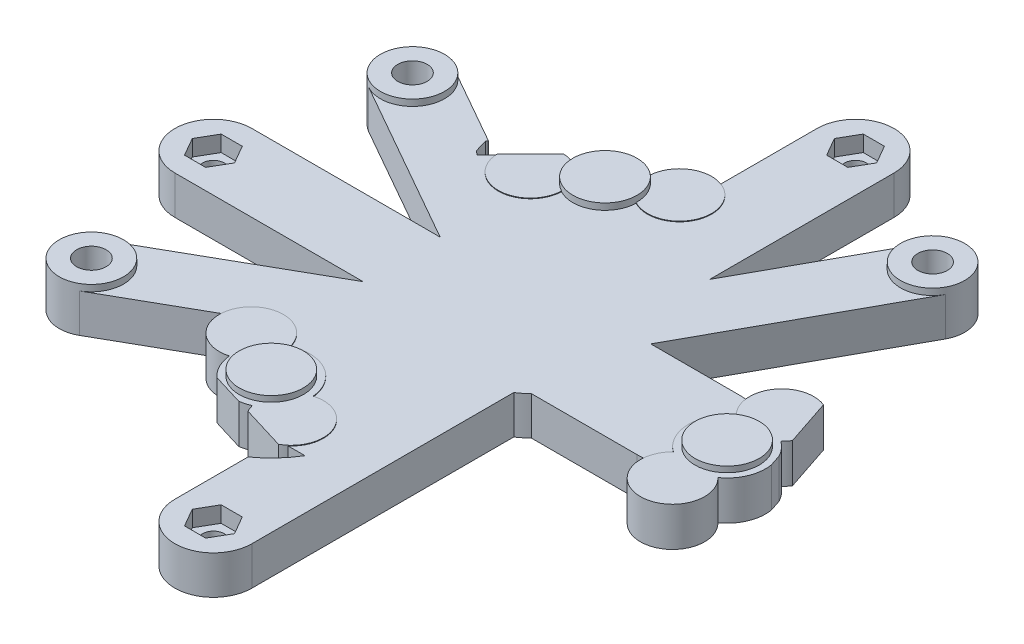
SolidWorks part; units mm, degrees
other "Fixed Star Plate Print Blank"
ref_plane "Front Plane" through (0, 0, 0) normal (0, 0, 1) x (1, 0, 0)
ref_plane "Top Plane" through (0, 0, 0) normal (0, 1, 0) x (1, 0, 0)
ref_plane "Right Plane" through (0, 0, 0) normal (1, 0, 0) x (0, 0, -1)
sketch3d "Base Outline Sketch datum points"
  point P0 (0, -71, 0)
  point P1 (10, -71, 0)
  point P2 (0, -71, -10)
ref_plane "Base Outline Sketch plane" through (0, -71, 0) normal (0, 1, 0) x (1, 0, 0)
sketch "Base Outline Sketch" plane through (0, -71, 0) normal (0, 1, 0) x (1, 0, 0)
  line L0 (-32.2917, 8) -> (-46.1853, 8)
  line L1 (-24.4227, 13.1376) -> (-22.0154, 5.909)
  line L2 (-20.9711, 2.7735) -> (-20.3706, 0.9703)
  line L3 (-48.7418, -8) -> (-32.2917, -8)
  line L4 (-50.2917, -50) -> (-50.2917, -9.2195)
  line L5 (-62.2917, -38.6002) -> (-62.2917, -50)
  line L6 (-58.0273, -34) -> (-60.6452, -34)
  line L7 (-61.5389, -34.6217) -> (-68.3642, -32.542)
  line L8 (-70.4166, -31.9166) -> (-75.3281, -30.42)
  line L9 (-97.8216, -29.3473) -> (-83.633, -21.2856)
  line L10 (-76.9729, -6) -> (-102.7617, -20.6527)
  line L11 (-106.2917, -6) -> (-76.9729, -6)
  line L12 (-76.9729, 6) -> (-106.2917, 6)
  line L13 (-102.7617, 20.6527) -> (-76.9729, 6)
  line L14 (-86.2562, 22.776) -> (-97.8216, 29.3473)
  line L15 (-86.2562, 22.776) -> (-86.3054, 22.6772)
  line L16 (-86.3054, 22.6772) -> (-86.3838, 22.4486)
  line L17 (-85.7572, 20.4132) -> (-85.2034, 19.9887)
  line L18 (-85.2034, 19.9887) -> (-83.8108, 21.3866)
  line L19 (-83.633, 21.2856) -> (-83.8108, 21.3866)
  line L20 (-83.6495, 21.5484) -> (-78.4893, 26.7281)
  line L21 (-62.2917, 50) -> (-62.2917, 34.9546)
  line L22 (-50.2917, 21.2843) -> (-50.2917, 50)
  line L23 (-38.6727, 42.4096) -> (-50.2917, 21.2843)
  line L24 (-46.1853, 8) -> (-29.9106, 37.5904)
  circle A0 centre (-71.2917, -25.9808) radius 3.95
  circle A1 centre (-63.9304, -30.2308) radius 1.6
  circle A2 centre (-26.2917, 0) radius 3.95
  circle A3 centre (-56.2917, -50) radius 3.1
  circle A4 centre (-26.2917, -8.5) radius 1.6
  circle A5 centre (-78.6529, -21.7308) radius 1.6
  circle A6 centre (-100.2917, -25) radius 2.3
  circle A7 centre (-71.2917, 25.9808) radius 3.95
  circle A8 centre (-34.2917, 40) radius 2.3
  circle A9 centre (-26.2917, 8.5) radius 1.6
  circle A10 centre (-63.9304, 30.2308) radius 1.6
  circle A11 centre (-56.2917, 50) radius 3.1
  circle A12 centre (-78.6529, 21.7308) radius 1.6
  circle A13 centre (-106.2917, 0) radius 3.1
  circle A14 centre (-100.2917, 25) radius 2.3
  arc A15 (-31.2594, 7.9331) -> (-32.2917, 8) centre (-32.2917, 0) ccw
  arc A16 (-24.4227, 13.1376) -> (-31.2594, 7.9331) centre (-26.2917, 8.5) ccw
  arc A17 (-22.8248, 4.8971) -> (-22.0154, 5.909) centre (-26.2917, 8.5) ccw
  arc A18 (-20.9711, 2.7735) -> (-22.8248, 4.8971) centre (-26.2917, 0) ccw
  arc A19 (-22.8248, -4.8971) -> (-20.3706, 0.9703) centre (-26.2917, 0) ccw
  arc A20 (-31.2594, -7.9331) -> (-22.8248, -4.8971) centre (-26.2917, -8.5) ccw
  arc A21 (-32.2917, -8) -> (-31.2594, -7.9331) centre (-32.2917, 0) ccw
  arc A22 (-50.2917, -9.2195) -> (-48.7418, -8) centre (-56.2917, 0) ccw
  arc A23 (-62.2917, -50) -> (-50.2917, -50) centre (-56.2917, -50) ccw
  arc A24 (-62.2917, -38.6002) -> (-58.0273, -34) centre (-71.2917, -25.9808) ccw
  arc A25 (-61.5389, -34.6217) -> (-60.6452, -34) centre (-63.9304, -30.2308) ccw
  arc A26 (-68.7841, -31.4316) -> (-68.3642, -32.542) centre (-63.9304, -30.2308) ccw
  arc A27 (-70.4166, -31.9166) -> (-68.7841, -31.4316) centre (-71.2917, -25.9808) ccw
  arc A28 (-77.266, -26.5346) -> (-75.3281, -30.42) centre (-71.2917, -25.9808) ccw
  arc A29 (-83.633, -21.2856) -> (-77.266, -26.5346) centre (-78.6529, -21.7308) ccw
  arc A30 (-100.2917, -30) -> (-97.8216, -29.3473) centre (-100.2917, -25) ccw
  arc A31 (-102.7617, -20.6527) -> (-100.2917, -30) centre (-100.2917, -25) ccw
  arc A32 (-106.2917, 6) -> (-106.2917, -6) centre (-106.2917, 0) ccw
  arc A33 (-97.8216, 29.3473) -> (-102.7617, 20.6527) centre (-100.2917, 25) ccw
  arc A34 (-86.3838, 22.4486) -> (-85.7572, 20.4132) centre (-71.2917, 25.9808) ccw
  arc A35 (-83.6495, 21.5484) -> (-83.633, 21.2856) centre (-78.6529, 21.7308) ccw
  arc A36 (-76.2892, 26.1368) -> (-78.4893, 26.7281) centre (-78.6529, 21.7308) ccw
  arc A37 (-68.928, 30.3868) -> (-76.2892, 26.1368) centre (-71.2917, 25.9808) ccw
  arc A38 (-68.7841, 31.4316) -> (-68.928, 30.3868) centre (-63.9304, 30.2308) ccw
  arc A39 (-62.2917, 34.9546) -> (-68.7841, 31.4316) centre (-63.9304, 30.2308) ccw
  arc A40 (-50.2917, 50) -> (-62.2917, 50) centre (-56.2917, 50) ccw
  arc A41 (-29.9106, 37.5904) -> (-38.6727, 42.4096) centre (-34.2917, 40) ccw
extrude "Base Outline" add sketch "Base Outline Sketch" along normal blind 1.4 separate body
sketch3d "Interface Profile 2 Sketch datum points"
  point P0 (0, -69.6, 0)
  point P1 (10, -69.6, 0)
  point P2 (0, -69.6, -10)
ref_plane "Interface Profile 2 Sketch plane" through (0, -69.6, 0) normal (0, 1, 0) x (1, 0, 0)
sketch "Interface Profile 2 Sketch" plane through (0, -69.6, 0) normal (0, 1, 0) x (1, 0, 0)
  line L0 (-32.2917, 8) -> (-46.1853, 8)
  line L1 (-24.4227, 13.1376) -> (-22.0154, 5.909)
  line L2 (-20.9711, 2.7735) -> (-20.3706, 0.9703)
  line L3 (-48.7418, -8) -> (-32.2917, -8)
  line L4 (-50.2917, -50) -> (-50.2917, -9.2195)
  line L5 (-62.2917, -38.6002) -> (-62.2917, -50)
  line L6 (-58.0273, -34) -> (-60.6452, -34)
  line L7 (-61.5389, -34.6217) -> (-68.3642, -32.542)
  line L8 (-70.4166, -31.9166) -> (-75.3281, -30.42)
  line L9 (-97.8216, -29.3473) -> (-83.633, -21.2856)
  line L10 (-76.9729, -6) -> (-102.7617, -20.6527)
  line L11 (-106.2917, -6) -> (-76.9729, -6)
  line L12 (-76.9729, 6) -> (-106.2917, 6)
  line L13 (-102.7617, 20.6527) -> (-76.9729, 6)
  line L14 (-86.2562, 22.776) -> (-97.8216, 29.3473)
  line L15 (-86.2562, 22.776) -> (-86.3054, 22.6772)
  line L16 (-86.3054, 22.6772) -> (-86.3838, 22.4486)
  line L17 (-85.7572, 20.4132) -> (-85.2034, 19.9887)
  line L18 (-85.2034, 19.9887) -> (-83.8108, 21.3866)
  line L19 (-83.633, 21.2856) -> (-83.8108, 21.3866)
  line L20 (-83.6495, 21.5484) -> (-78.4893, 26.7281)
  line L21 (-62.2917, 50) -> (-62.2917, 34.9546)
  line L22 (-50.2917, 21.2843) -> (-50.2917, 50)
  line L23 (-38.6727, 42.4096) -> (-50.2917, 21.2843)
  line L24 (-46.1853, 8) -> (-29.9106, 37.5904)
  circle A0 centre (-71.2917, -25.9808) radius 3.95
  circle A1 centre (-63.9304, -30.2308) radius 1.6
  circle A2 centre (-26.2917, 0) radius 3.95
  circle A3 centre (-56.2917, -50) radius 1.7
  circle A4 centre (-56.2917, 50) radius 1.7
  circle A5 centre (-106.2917, 0) radius 1.7
  circle A6 centre (-26.2917, -8.5) radius 1.6
  circle A7 centre (-78.6529, -21.7308) radius 1.6
  circle A8 centre (-100.2917, -25) radius 2.3
  circle A9 centre (-71.2917, 25.9808) radius 3.95
  circle A10 centre (-34.2917, 40) radius 2.3
  circle A11 centre (-26.2917, 8.5) radius 1.6
  circle A12 centre (-63.9304, 30.2308) radius 1.6
  circle A13 centre (-78.6529, 21.7308) radius 1.6
  circle A14 centre (-100.2917, 25) radius 2.3
  arc A15 (-31.2594, 7.9331) -> (-32.2917, 8) centre (-32.2917, 0) ccw
  arc A16 (-24.4227, 13.1376) -> (-31.2594, 7.9331) centre (-26.2917, 8.5) ccw
  arc A17 (-22.8248, 4.8971) -> (-22.0154, 5.909) centre (-26.2917, 8.5) ccw
  arc A18 (-20.9711, 2.7735) -> (-22.8248, 4.8971) centre (-26.2917, 0) ccw
  arc A19 (-22.8248, -4.8971) -> (-20.3706, 0.9703) centre (-26.2917, 0) ccw
  arc A20 (-31.2594, -7.9331) -> (-22.8248, -4.8971) centre (-26.2917, -8.5) ccw
  arc A21 (-32.2917, -8) -> (-31.2594, -7.9331) centre (-32.2917, 0) ccw
  arc A22 (-50.2917, -9.2195) -> (-48.7418, -8) centre (-56.2917, 0) ccw
  arc A23 (-62.2917, -50) -> (-50.2917, -50) centre (-56.2917, -50) ccw
  arc A24 (-62.2917, -38.6002) -> (-58.0273, -34) centre (-71.2917, -25.9808) ccw
  arc A25 (-61.5389, -34.6217) -> (-60.6452, -34) centre (-63.9304, -30.2308) ccw
  arc A26 (-68.7841, -31.4316) -> (-68.3642, -32.542) centre (-63.9304, -30.2308) ccw
  arc A27 (-70.4166, -31.9166) -> (-68.7841, -31.4316) centre (-71.2917, -25.9808) ccw
  arc A28 (-77.266, -26.5346) -> (-75.3281, -30.42) centre (-71.2917, -25.9808) ccw
  arc A29 (-83.633, -21.2856) -> (-77.266, -26.5346) centre (-78.6529, -21.7308) ccw
  arc A30 (-100.2917, -30) -> (-97.8216, -29.3473) centre (-100.2917, -25) ccw
  arc A31 (-102.7617, -20.6527) -> (-100.2917, -30) centre (-100.2917, -25) ccw
  arc A32 (-106.2917, 6) -> (-106.2917, -6) centre (-106.2917, 0) ccw
  arc A33 (-97.8216, 29.3473) -> (-102.7617, 20.6527) centre (-100.2917, 25) ccw
  arc A34 (-86.3838, 22.4486) -> (-85.7572, 20.4132) centre (-71.2917, 25.9808) ccw
  arc A35 (-83.6495, 21.5484) -> (-83.633, 21.2856) centre (-78.6529, 21.7308) ccw
  arc A36 (-76.2892, 26.1368) -> (-78.4893, 26.7281) centre (-78.6529, 21.7308) ccw
  arc A37 (-68.928, 30.3868) -> (-76.2892, 26.1368) centre (-71.2917, 25.9808) ccw
  arc A38 (-68.7841, 31.4316) -> (-68.928, 30.3868) centre (-63.9304, 30.2308) ccw
  arc A39 (-62.2917, 34.9546) -> (-68.7841, 31.4316) centre (-63.9304, 30.2308) ccw
  arc A40 (-50.2917, 50) -> (-62.2917, 50) centre (-56.2917, 50) ccw
  arc A41 (-29.9106, 37.5904) -> (-38.6727, 42.4096) centre (-34.2917, 40) ccw
extrude "Interface Profile 2" add sketch "Interface Profile 2 Sketch" along normal blind 0.1
sketch3d "Interface Profile 3 Sketch datum points"
  point P0 (0, -69.5, 0)
  point P1 (10, -69.5, 0)
  point P2 (0, -69.5, -10)
ref_plane "Interface Profile 3 Sketch plane" through (0, -69.5, 0) normal (0, 1, 0) x (1, 0, 0)
sketch "Interface Profile 3 Sketch" plane through (0, -69.5, 0) normal (0, 1, 0) x (1, 0, 0)
  line L0 (-70.8027, -29.9004) -> (-74.9306, -27.5171)
  line L1 (-23.1417, 2.3833) -> (-23.1417, -2.3833)
  line L2 (-74.9306, 27.5171) -> (-70.8027, 29.9004)
  line L3 (-32.2917, 8) -> (-46.1853, 8)
  line L4 (-24.4227, 13.1376) -> (-22.0154, 5.909)
  line L5 (-20.9711, 2.7735) -> (-20.3706, 0.9703)
  line L6 (-48.7418, -8) -> (-32.2917, -8)
  line L7 (-50.2917, -50) -> (-50.2917, -9.2195)
  line L8 (-62.2917, -38.6002) -> (-62.2917, -50)
  line L9 (-58.0273, -34) -> (-60.6452, -34)
  line L10 (-61.5389, -34.6217) -> (-68.3642, -32.542)
  line L11 (-70.4166, -31.9166) -> (-75.3281, -30.42)
  line L12 (-97.8216, -29.3473) -> (-83.633, -21.2856)
  line L13 (-76.9729, -6) -> (-102.7617, -20.6527)
  line L14 (-106.2917, -6) -> (-76.9729, -6)
  line L15 (-76.9729, 6) -> (-106.2917, 6)
  line L16 (-102.7617, 20.6527) -> (-76.9729, 6)
  line L17 (-86.2562, 22.776) -> (-97.8216, 29.3473)
  line L18 (-86.2562, 22.776) -> (-86.3054, 22.6772)
  line L19 (-86.3054, 22.6772) -> (-86.3838, 22.4486)
  line L20 (-85.7572, 20.4132) -> (-85.2034, 19.9887)
  line L21 (-85.2034, 19.9887) -> (-83.8108, 21.3866)
  line L22 (-83.633, 21.2856) -> (-83.8108, 21.3866)
  line L23 (-83.6495, 21.5484) -> (-78.4893, 26.7281)
  line L24 (-62.2917, 50) -> (-62.2917, 34.9546)
  line L25 (-50.2917, 21.2843) -> (-50.2917, 50)
  line L26 (-38.6727, 42.4096) -> (-50.2917, 21.2843)
  line L27 (-46.1853, 8) -> (-29.9106, 37.5904)
  arc A0 (-67.3417, -25.9808) -> (-70.8027, -29.9004) centre (-71.2917, -25.9808) cw
  arc A1 (-74.9306, -27.5171) -> (-67.3417, -25.9808) centre (-71.2917, -25.9808) cw
  circle A2 centre (-63.9304, -30.2308) radius 1.6
  arc A3 (-23.1417, -2.3833) -> (-23.1417, 2.3833) centre (-26.2917, 0) cw
  circle A4 centre (-56.2917, -50) radius 1.7
  circle A5 centre (-56.2917, 50) radius 1.7
  circle A6 centre (-106.2917, 0) radius 1.7
  circle A7 centre (-26.2917, -8.5) radius 1.6
  circle A8 centre (-78.6529, -21.7308) radius 1.6
  circle A9 centre (-100.2917, -25) radius 2.3
  arc A10 (-67.3417, 25.9808) -> (-74.9306, 27.5171) centre (-71.2917, 25.9808) cw
  arc A11 (-70.8027, 29.9004) -> (-67.3417, 25.9808) centre (-71.2917, 25.9808) cw
  circle A12 centre (-34.2917, 40) radius 2.3
  circle A13 centre (-26.2917, 8.5) radius 1.6
  circle A14 centre (-63.9304, 30.2308) radius 1.6
  circle A15 centre (-78.6529, 21.7308) radius 1.6
  circle A16 centre (-100.2917, 25) radius 2.3
  arc A17 (-31.2594, 7.9331) -> (-32.2917, 8) centre (-32.2917, 0) ccw
  arc A18 (-24.4227, 13.1376) -> (-31.2594, 7.9331) centre (-26.2917, 8.5) ccw
  arc A19 (-22.8248, 4.8971) -> (-22.0154, 5.909) centre (-26.2917, 8.5) ccw
  arc A20 (-20.9711, 2.7735) -> (-22.8248, 4.8971) centre (-26.2917, 0) ccw
  arc A21 (-22.8248, -4.8971) -> (-20.3706, 0.9703) centre (-26.2917, 0) ccw
  arc A22 (-31.2594, -7.9331) -> (-22.8248, -4.8971) centre (-26.2917, -8.5) ccw
  arc A23 (-32.2917, -8) -> (-31.2594, -7.9331) centre (-32.2917, 0) ccw
  arc A24 (-50.2917, -9.2195) -> (-48.7418, -8) centre (-56.2917, 0) ccw
  arc A25 (-62.2917, -50) -> (-50.2917, -50) centre (-56.2917, -50) ccw
  arc A26 (-62.2917, -38.6002) -> (-58.0273, -34) centre (-71.2917, -25.9808) ccw
  arc A27 (-61.5389, -34.6217) -> (-60.6452, -34) centre (-63.9304, -30.2308) ccw
  arc A28 (-68.7841, -31.4316) -> (-68.3642, -32.542) centre (-63.9304, -30.2308) ccw
  arc A29 (-70.4166, -31.9166) -> (-68.7841, -31.4316) centre (-71.2917, -25.9808) ccw
  arc A30 (-77.266, -26.5346) -> (-75.3281, -30.42) centre (-71.2917, -25.9808) ccw
  arc A31 (-83.633, -21.2856) -> (-77.266, -26.5346) centre (-78.6529, -21.7308) ccw
  arc A32 (-100.2917, -30) -> (-97.8216, -29.3473) centre (-100.2917, -25) ccw
  arc A33 (-102.7617, -20.6527) -> (-100.2917, -30) centre (-100.2917, -25) ccw
  arc A34 (-106.2917, 6) -> (-106.2917, -6) centre (-106.2917, 0) ccw
  arc A35 (-97.8216, 29.3473) -> (-102.7617, 20.6527) centre (-100.2917, 25) ccw
  arc A36 (-86.3838, 22.4486) -> (-85.7572, 20.4132) centre (-71.2917, 25.9808) ccw
  arc A37 (-83.6495, 21.5484) -> (-83.633, 21.2856) centre (-78.6529, 21.7308) ccw
  arc A38 (-76.2892, 26.1368) -> (-78.4893, 26.7281) centre (-78.6529, 21.7308) ccw
  arc A39 (-68.928, 30.3868) -> (-76.2892, 26.1368) centre (-71.2917, 25.9808) ccw
  arc A40 (-68.7841, 31.4316) -> (-68.928, 30.3868) centre (-63.9304, 30.2308) ccw
  arc A41 (-62.2917, 34.9546) -> (-68.7841, 31.4316) centre (-63.9304, 30.2308) ccw
  arc A42 (-50.2917, 50) -> (-62.2917, 50) centre (-56.2917, 50) ccw
  arc A43 (-29.9106, 37.5904) -> (-38.6727, 42.4096) centre (-34.2917, 40) ccw
extrude "Interface Profile 3" add sketch "Interface Profile 3 Sketch" along normal blind 0.5
sketch3d "Interface Profile 4 Sketch datum points"
  point P0 (0, -69, 0)
  point P1 (10, -69, 0)
  point P2 (0, -69, -10)
ref_plane "Interface Profile 4 Sketch plane" through (0, -69, 0) normal (0, 1, 0) x (1, 0, 0)
sketch "Interface Profile 4 Sketch" plane through (0, -69, 0) normal (0, 1, 0) x (1, 0, 0)
  line L0 (-32.2917, 8) -> (-46.1853, 8)
  line L1 (-24.4227, 13.1376) -> (-22.0154, 5.909)
  line L2 (-20.9711, 2.7735) -> (-20.3706, 0.9703)
  line L3 (-48.7418, -8) -> (-32.2917, -8)
  line L4 (-50.2917, -50) -> (-50.2917, -9.2195)
  line L5 (-62.2917, -38.6002) -> (-62.2917, -50)
  line L6 (-58.0273, -34) -> (-60.6452, -34)
  line L7 (-61.5389, -34.6217) -> (-68.3642, -32.542)
  line L8 (-70.4166, -31.9166) -> (-75.3281, -30.42)
  line L9 (-97.8216, -29.3473) -> (-83.633, -21.2856)
  line L10 (-76.9729, -6) -> (-102.7617, -20.6527)
  line L11 (-106.2917, -6) -> (-76.9729, -6)
  line L12 (-76.9729, 6) -> (-106.2917, 6)
  line L13 (-102.7617, 20.6527) -> (-76.9729, 6)
  line L14 (-86.2562, 22.776) -> (-97.8216, 29.3473)
  line L15 (-86.2562, 22.776) -> (-86.3054, 22.6772)
  line L16 (-86.3054, 22.6772) -> (-86.3838, 22.4486)
  line L17 (-85.7572, 20.4132) -> (-85.2034, 19.9887)
  line L18 (-85.2034, 19.9887) -> (-83.8108, 21.3866)
  line L19 (-83.633, 21.2856) -> (-83.8108, 21.3866)
  line L20 (-83.6495, 21.5484) -> (-78.4893, 26.7281)
  line L21 (-62.2917, 50) -> (-62.2917, 34.9546)
  line L22 (-50.2917, 21.2843) -> (-50.2917, 50)
  line L23 (-38.6727, 42.4096) -> (-50.2917, 21.2843)
  line L24 (-46.1853, 8) -> (-29.9106, 37.5904)
  circle A0 centre (-63.9304, -30.2308) radius 1.6
  circle A1 centre (-56.2917, -50) radius 1.7
  circle A2 centre (-56.2917, 50) radius 1.7
  circle A3 centre (-106.2917, 0) radius 1.7
  circle A4 centre (-26.2917, -8.5) radius 1.6
  circle A5 centre (-78.6529, -21.7308) radius 1.6
  circle A6 centre (-100.2917, -25) radius 2.3
  circle A7 centre (-34.2917, 40) radius 2.3
  circle A8 centre (-26.2917, 8.5) radius 1.6
  circle A9 centre (-63.9304, 30.2308) radius 1.6
  circle A10 centre (-78.6529, 21.7308) radius 1.6
  circle A11 centre (-100.2917, 25) radius 2.3
  arc A12 (-31.2594, 7.9331) -> (-32.2917, 8) centre (-32.2917, 0) ccw
  arc A13 (-24.4227, 13.1376) -> (-31.2594, 7.9331) centre (-26.2917, 8.5) ccw
  arc A14 (-22.8248, 4.8971) -> (-22.0154, 5.909) centre (-26.2917, 8.5) ccw
  arc A15 (-20.9711, 2.7735) -> (-22.8248, 4.8971) centre (-26.2917, 0) ccw
  arc A16 (-22.8248, -4.8971) -> (-20.3706, 0.9703) centre (-26.2917, 0) ccw
  arc A17 (-31.2594, -7.9331) -> (-22.8248, -4.8971) centre (-26.2917, -8.5) ccw
  arc A18 (-32.2917, -8) -> (-31.2594, -7.9331) centre (-32.2917, 0) ccw
  arc A19 (-50.2917, -9.2195) -> (-48.7418, -8) centre (-56.2917, 0) ccw
  arc A20 (-62.2917, -50) -> (-50.2917, -50) centre (-56.2917, -50) ccw
  arc A21 (-62.2917, -38.6002) -> (-58.0273, -34) centre (-71.2917, -25.9808) ccw
  arc A22 (-61.5389, -34.6217) -> (-60.6452, -34) centre (-63.9304, -30.2308) ccw
  arc A23 (-68.7841, -31.4316) -> (-68.3642, -32.542) centre (-63.9304, -30.2308) ccw
  arc A24 (-70.4166, -31.9166) -> (-68.7841, -31.4316) centre (-71.2917, -25.9808) ccw
  arc A25 (-77.266, -26.5346) -> (-75.3281, -30.42) centre (-71.2917, -25.9808) ccw
  arc A26 (-83.633, -21.2856) -> (-77.266, -26.5346) centre (-78.6529, -21.7308) ccw
  arc A27 (-100.2917, -30) -> (-97.8216, -29.3473) centre (-100.2917, -25) ccw
  arc A28 (-102.7617, -20.6527) -> (-100.2917, -30) centre (-100.2917, -25) ccw
  arc A29 (-106.2917, 6) -> (-106.2917, -6) centre (-106.2917, 0) ccw
  arc A30 (-97.8216, 29.3473) -> (-102.7617, 20.6527) centre (-100.2917, 25) ccw
  arc A31 (-86.3838, 22.4486) -> (-85.7572, 20.4132) centre (-71.2917, 25.9808) ccw
  arc A32 (-83.6495, 21.5484) -> (-83.633, 21.2856) centre (-78.6529, 21.7308) ccw
  arc A33 (-76.2892, 26.1368) -> (-78.4893, 26.7281) centre (-78.6529, 21.7308) ccw
  arc A34 (-68.928, 30.3868) -> (-76.2892, 26.1368) centre (-71.2917, 25.9808) ccw
  arc A35 (-68.7841, 31.4316) -> (-68.928, 30.3868) centre (-63.9304, 30.2308) ccw
  arc A36 (-62.2917, 34.9546) -> (-68.7841, 31.4316) centre (-63.9304, 30.2308) ccw
  arc A37 (-50.2917, 50) -> (-62.2917, 50) centre (-56.2917, 50) ccw
  arc A38 (-29.9106, 37.5904) -> (-38.6727, 42.4096) centre (-34.2917, 40) ccw
extrude "Interface Profile 4" add sketch "Interface Profile 4 Sketch" along normal blind 1.5
sketch3d "Interface Profile 5 Sketch datum points"
  point P0 (0, -67.5, 0)
  point P1 (10, -67.5, 0)
  point P2 (0, -67.5, -10)
ref_plane "Interface Profile 5 Sketch plane" through (0, -67.5, 0) normal (0, 1, 0) x (1, 0, 0)
sketch "Interface Profile 5 Sketch" plane through (0, -67.5, 0) normal (0, 1, 0) x (1, 0, 0)
  line L0 (-59.5825, -50) -> (-57.9371, -47.15)
  line L1 (-57.9371, -52.85) -> (-59.5825, -50)
  line L2 (-57.9371, -47.15) -> (-54.6462, -47.15)
  line L3 (-54.6462, 52.85) -> (-53.0008, 50)
  line L4 (-57.9371, 52.85) -> (-54.6462, 52.85)
  line L5 (-53.0008, 50) -> (-54.6462, 47.15)
  line L6 (-59.5825, 50) -> (-57.9371, 52.85)
  line L7 (-57.9371, 47.15) -> (-59.5825, 50)
  line L8 (-54.6462, 47.15) -> (-57.9371, 47.15)
  line L9 (-104.6462, 2.85) -> (-103.0008, 0)
  line L10 (-107.9371, 2.85) -> (-104.6462, 2.85)
  line L11 (-103.0008, 0) -> (-104.6462, -2.85)
  line L12 (-109.5825, 0) -> (-107.9371, 2.85)
  line L13 (-107.9371, -2.85) -> (-109.5825, 0)
  line L14 (-104.6462, -2.85) -> (-107.9371, -2.85)
  line L15 (-54.6462, -52.85) -> (-57.9371, -52.85)
  line L16 (-54.6462, -47.15) -> (-53.0008, -50)
  line L17 (-53.0008, -50) -> (-54.6462, -52.85)
  line L18 (-32.2917, 8) -> (-46.1853, 8)
  line L19 (-24.4227, 13.1376) -> (-22.0154, 5.909)
  line L20 (-20.9711, 2.7735) -> (-20.3706, 0.9703)
  line L21 (-48.7418, -8) -> (-32.2917, -8)
  line L22 (-50.2917, -50) -> (-50.2917, -9.2195)
  line L23 (-62.2917, -38.6002) -> (-62.2917, -50)
  line L24 (-58.0273, -34) -> (-60.6452, -34)
  line L25 (-61.5389, -34.6217) -> (-68.3642, -32.542)
  line L26 (-70.4166, -31.9166) -> (-75.3281, -30.42)
  line L27 (-97.8216, -29.3473) -> (-83.633, -21.2856)
  line L28 (-76.9729, -6) -> (-102.7617, -20.6527)
  line L29 (-106.2917, -6) -> (-76.9729, -6)
  line L30 (-76.9729, 6) -> (-106.2917, 6)
  line L31 (-102.7617, 20.6527) -> (-76.9729, 6)
  line L32 (-86.2562, 22.776) -> (-97.8216, 29.3473)
  line L33 (-86.2562, 22.776) -> (-86.3054, 22.6772)
  line L34 (-86.3054, 22.6772) -> (-86.3838, 22.4486)
  line L35 (-85.7572, 20.4132) -> (-85.2034, 19.9887)
  line L36 (-85.2034, 19.9887) -> (-83.8108, 21.3866)
  line L37 (-83.633, 21.2856) -> (-83.8108, 21.3866)
  line L38 (-83.6495, 21.5484) -> (-78.4893, 26.7281)
  line L39 (-62.2917, 50) -> (-62.2917, 34.9546)
  line L40 (-50.2917, 21.2843) -> (-50.2917, 50)
  line L41 (-38.6727, 42.4096) -> (-50.2917, 21.2843)
  line L42 (-46.1853, 8) -> (-29.9106, 37.5904)
  circle A0 centre (-63.9304, -30.2308) radius 1.6
  circle A1 centre (-26.2917, -8.5) radius 1.6
  circle A2 centre (-78.6529, -21.7308) radius 1.6
  circle A3 centre (-100.2917, -25) radius 2.3
  circle A4 centre (-34.2917, 40) radius 2.3
  circle A5 centre (-26.2917, 8.5) radius 1.6
  circle A6 centre (-63.9304, 30.2308) radius 1.6
  circle A7 centre (-78.6529, 21.7308) radius 1.6
  circle A8 centre (-100.2917, 25) radius 2.3
  arc A9 (-31.2594, 7.9331) -> (-32.2917, 8) centre (-32.2917, 0) ccw
  arc A10 (-24.4227, 13.1376) -> (-31.2594, 7.9331) centre (-26.2917, 8.5) ccw
  arc A11 (-22.8248, 4.8971) -> (-22.0154, 5.909) centre (-26.2917, 8.5) ccw
  arc A12 (-20.9711, 2.7735) -> (-22.8248, 4.8971) centre (-26.2917, 0) ccw
  arc A13 (-22.8248, -4.8971) -> (-20.3706, 0.9703) centre (-26.2917, 0) ccw
  arc A14 (-31.2594, -7.9331) -> (-22.8248, -4.8971) centre (-26.2917, -8.5) ccw
  arc A15 (-32.2917, -8) -> (-31.2594, -7.9331) centre (-32.2917, 0) ccw
  arc A16 (-50.2917, -9.2195) -> (-48.7418, -8) centre (-56.2917, 0) ccw
  arc A17 (-62.2917, -50) -> (-50.2917, -50) centre (-56.2917, -50) ccw
  arc A18 (-62.2917, -38.6002) -> (-58.0273, -34) centre (-71.2917, -25.9808) ccw
  arc A19 (-61.5389, -34.6217) -> (-60.6452, -34) centre (-63.9304, -30.2308) ccw
  arc A20 (-68.7841, -31.4316) -> (-68.3642, -32.542) centre (-63.9304, -30.2308) ccw
  arc A21 (-70.4166, -31.9166) -> (-68.7841, -31.4316) centre (-71.2917, -25.9808) ccw
  arc A22 (-77.266, -26.5346) -> (-75.3281, -30.42) centre (-71.2917, -25.9808) ccw
  arc A23 (-83.633, -21.2856) -> (-77.266, -26.5346) centre (-78.6529, -21.7308) ccw
  arc A24 (-100.2917, -30) -> (-97.8216, -29.3473) centre (-100.2917, -25) ccw
  arc A25 (-102.7617, -20.6527) -> (-100.2917, -30) centre (-100.2917, -25) ccw
  arc A26 (-106.2917, 6) -> (-106.2917, -6) centre (-106.2917, 0) ccw
  arc A27 (-97.8216, 29.3473) -> (-102.7617, 20.6527) centre (-100.2917, 25) ccw
  arc A28 (-86.3838, 22.4486) -> (-85.7572, 20.4132) centre (-71.2917, 25.9808) ccw
  arc A29 (-83.6495, 21.5484) -> (-83.633, 21.2856) centre (-78.6529, 21.7308) ccw
  arc A30 (-76.2892, 26.1368) -> (-78.4893, 26.7281) centre (-78.6529, 21.7308) ccw
  arc A31 (-68.928, 30.3868) -> (-76.2892, 26.1368) centre (-71.2917, 25.9808) ccw
  arc A32 (-68.7841, 31.4316) -> (-68.928, 30.3868) centre (-63.9304, 30.2308) ccw
  arc A33 (-62.2917, 34.9546) -> (-68.7841, 31.4316) centre (-63.9304, 30.2308) ccw
  arc A34 (-50.2917, 50) -> (-62.2917, 50) centre (-56.2917, 50) ccw
  arc A35 (-29.9106, 37.5904) -> (-38.6727, 42.4096) centre (-34.2917, 40) ccw
extrude "Interface Profile 5" add sketch "Interface Profile 5 Sketch" along normal blind 0.5
sketch3d "Interface Profile 6 Sketch datum points"
  point P0 (0, -67, 0)
  point P1 (10, -67, 0)
  point P2 (0, -67, -10)
ref_plane "Interface Profile 6 Sketch plane" through (0, -67, 0) normal (0, 1, 0) x (1, 0, 0)
sketch "Interface Profile 6 Sketch" plane through (0, -67, 0) normal (0, 1, 0) x (1, 0, 0)
  line L0 (-59.5825, -50) -> (-57.9371, -47.15)
  line L1 (-57.9371, -52.85) -> (-59.5825, -50)
  line L2 (-57.9371, -47.15) -> (-54.6462, -47.15)
  line L3 (-54.6462, 52.85) -> (-53.0008, 50)
  line L4 (-57.9371, 52.85) -> (-54.6462, 52.85)
  line L5 (-53.0008, 50) -> (-54.6462, 47.15)
  line L6 (-59.5825, 50) -> (-57.9371, 52.85)
  line L7 (-57.9371, 47.15) -> (-59.5825, 50)
  line L8 (-54.6462, 47.15) -> (-57.9371, 47.15)
  line L9 (-104.6462, 2.85) -> (-103.0008, 0)
  line L10 (-107.9371, 2.85) -> (-104.6462, 2.85)
  line L11 (-103.0008, 0) -> (-104.6462, -2.85)
  line L12 (-109.5825, 0) -> (-107.9371, 2.85)
  line L13 (-107.9371, -2.85) -> (-109.5825, 0)
  line L14 (-104.6462, -2.85) -> (-107.9371, -2.85)
  line L15 (-54.6462, -52.85) -> (-57.9371, -52.85)
  line L16 (-54.6462, -47.15) -> (-53.0008, -50)
  line L17 (-53.0008, -50) -> (-54.6462, -52.85)
  line L18 (-32.2917, 8) -> (-46.1853, 8)
  line L19 (-24.4227, 13.1376) -> (-22.0154, 5.909)
  line L20 (-20.9711, 2.7735) -> (-20.3706, 0.9703)
  line L21 (-48.7418, -8) -> (-32.2917, -8)
  line L22 (-50.2917, -50) -> (-50.2917, -9.2195)
  line L23 (-62.2917, -38.6002) -> (-62.2917, -50)
  line L24 (-58.0273, -34) -> (-60.6452, -34)
  line L25 (-61.5389, -34.6217) -> (-68.3642, -32.542)
  line L26 (-70.4166, -31.9166) -> (-75.3281, -30.42)
  line L27 (-97.8216, -29.3473) -> (-83.633, -21.2856)
  line L28 (-76.9729, -6) -> (-102.7617, -20.6527)
  line L29 (-106.2917, -6) -> (-76.9729, -6)
  line L30 (-76.9729, 6) -> (-106.2917, 6)
  line L31 (-102.7617, 20.6527) -> (-76.9729, 6)
  line L32 (-86.2562, 22.776) -> (-97.8216, 29.3473)
  line L33 (-86.2562, 22.776) -> (-86.3054, 22.6772)
  line L34 (-86.3054, 22.6772) -> (-86.3838, 22.4486)
  line L35 (-85.7572, 20.4132) -> (-85.2034, 19.9887)
  line L36 (-85.2034, 19.9887) -> (-83.8108, 21.3866)
  line L37 (-83.633, 21.2856) -> (-83.8108, 21.3866)
  line L38 (-83.6495, 21.5484) -> (-78.4893, 26.7281)
  line L39 (-62.2917, 50) -> (-62.2917, 34.9546)
  line L40 (-50.2917, 21.2843) -> (-50.2917, 50)
  line L41 (-38.6727, 42.4096) -> (-50.2917, 21.2843)
  line L42 (-46.1853, 8) -> (-29.9106, 37.5904)
  circle A0 centre (-63.9304, -30.2308) radius 1.1
  circle A1 centre (-26.2917, -8.5) radius 1.1
  circle A2 centre (-78.6529, -21.7308) radius 1.1
  circle A3 centre (-100.2917, -25) radius 2.3
  circle A4 centre (-34.2917, 40) radius 2.3
  circle A5 centre (-26.2917, 8.5) radius 1.1
  circle A6 centre (-63.9304, 30.2308) radius 1.1
  circle A7 centre (-78.6529, 21.7308) radius 1.1
  circle A8 centre (-100.2917, 25) radius 2.3
  arc A9 (-31.2594, 7.9331) -> (-32.2917, 8) centre (-32.2917, 0) ccw
  arc A10 (-24.4227, 13.1376) -> (-31.2594, 7.9331) centre (-26.2917, 8.5) ccw
  arc A11 (-22.8248, 4.8971) -> (-22.0154, 5.909) centre (-26.2917, 8.5) ccw
  arc A12 (-20.9711, 2.7735) -> (-22.8248, 4.8971) centre (-26.2917, 0) ccw
  arc A13 (-22.8248, -4.8971) -> (-20.3706, 0.9703) centre (-26.2917, 0) ccw
  arc A14 (-31.2594, -7.9331) -> (-22.8248, -4.8971) centre (-26.2917, -8.5) ccw
  arc A15 (-32.2917, -8) -> (-31.2594, -7.9331) centre (-32.2917, 0) ccw
  arc A16 (-50.2917, -9.2195) -> (-48.7418, -8) centre (-56.2917, 0) ccw
  arc A17 (-62.2917, -50) -> (-50.2917, -50) centre (-56.2917, -50) ccw
  arc A18 (-62.2917, -38.6002) -> (-58.0273, -34) centre (-71.2917, -25.9808) ccw
  arc A19 (-61.5389, -34.6217) -> (-60.6452, -34) centre (-63.9304, -30.2308) ccw
  arc A20 (-68.7841, -31.4316) -> (-68.3642, -32.542) centre (-63.9304, -30.2308) ccw
  arc A21 (-70.4166, -31.9166) -> (-68.7841, -31.4316) centre (-71.2917, -25.9808) ccw
  arc A22 (-77.266, -26.5346) -> (-75.3281, -30.42) centre (-71.2917, -25.9808) ccw
  arc A23 (-83.633, -21.2856) -> (-77.266, -26.5346) centre (-78.6529, -21.7308) ccw
  arc A24 (-100.2917, -30) -> (-97.8216, -29.3473) centre (-100.2917, -25) ccw
  arc A25 (-102.7617, -20.6527) -> (-100.2917, -30) centre (-100.2917, -25) ccw
  arc A26 (-106.2917, 6) -> (-106.2917, -6) centre (-106.2917, 0) ccw
  arc A27 (-97.8216, 29.3473) -> (-102.7617, 20.6527) centre (-100.2917, 25) ccw
  arc A28 (-86.3838, 22.4486) -> (-85.7572, 20.4132) centre (-71.2917, 25.9808) ccw
  arc A29 (-83.6495, 21.5484) -> (-83.633, 21.2856) centre (-78.6529, 21.7308) ccw
  arc A30 (-76.2892, 26.1368) -> (-78.4893, 26.7281) centre (-78.6529, 21.7308) ccw
  arc A31 (-68.928, 30.3868) -> (-76.2892, 26.1368) centre (-71.2917, 25.9808) ccw
  arc A32 (-68.7841, 31.4316) -> (-68.928, 30.3868) centre (-63.9304, 30.2308) ccw
  arc A33 (-62.2917, 34.9546) -> (-68.7841, 31.4316) centre (-63.9304, 30.2308) ccw
  arc A34 (-50.2917, 50) -> (-62.2917, 50) centre (-56.2917, 50) ccw
  arc A35 (-29.9106, 37.5904) -> (-38.6727, 42.4096) centre (-34.2917, 40) ccw
extrude "Interface Profile 6" add sketch "Interface Profile 6 Sketch" along normal blind 1.3
sketch3d "Interface Profile 7 Sketch datum points"
  point P0 (0, -65.7, 0)
  point P1 (10, -65.7, 0)
  point P2 (0, -65.7, -10)
ref_plane "Interface Profile 7 Sketch plane" through (0, -65.7, 0) normal (0, 1, 0) x (1, 0, 0)
sketch "Interface Profile 7 Sketch" plane through (0, -65.7, 0) normal (0, 1, 0) x (1, 0, 0)
  line L0 (-59.5825, -50) -> (-57.9371, -47.15)
  line L1 (-57.9371, -52.85) -> (-59.5825, -50)
  line L2 (-57.9371, -47.15) -> (-54.6462, -47.15)
  line L3 (-54.6462, 52.85) -> (-53.0008, 50)
  line L4 (-57.9371, 52.85) -> (-54.6462, 52.85)
  line L5 (-53.0008, 50) -> (-54.6462, 47.15)
  line L6 (-59.5825, 50) -> (-57.9371, 52.85)
  line L7 (-57.9371, 47.15) -> (-59.5825, 50)
  line L8 (-54.6462, 47.15) -> (-57.9371, 47.15)
  line L9 (-104.6462, 2.85) -> (-103.0008, 0)
  line L10 (-107.9371, 2.85) -> (-104.6462, 2.85)
  line L11 (-103.0008, 0) -> (-104.6462, -2.85)
  line L12 (-109.5825, 0) -> (-107.9371, 2.85)
  line L13 (-107.9371, -2.85) -> (-109.5825, 0)
  line L14 (-104.6462, -2.85) -> (-107.9371, -2.85)
  line L15 (-54.6462, -52.85) -> (-57.9371, -52.85)
  line L16 (-54.6462, -47.15) -> (-53.0008, -50)
  line L17 (-53.0008, -50) -> (-54.6462, -52.85)
  line L18 (-32.2917, 8) -> (-46.1853, 8)
  line L19 (-24.4227, 13.1376) -> (-22.0154, 5.909)
  line L20 (-20.9711, 2.7735) -> (-20.3706, 0.9703)
  line L21 (-48.7418, -8) -> (-32.2917, -8)
  line L22 (-50.2917, -50) -> (-50.2917, -9.2195)
  line L23 (-62.2917, -38.6002) -> (-62.2917, -50)
  line L24 (-58.0273, -34) -> (-60.6452, -34)
  line L25 (-61.5389, -34.6217) -> (-68.3642, -32.542)
  line L26 (-70.4166, -31.9166) -> (-75.3281, -30.42)
  line L27 (-97.8216, -29.3473) -> (-83.633, -21.2856)
  line L28 (-76.9729, -6) -> (-102.7617, -20.6527)
  line L29 (-106.2917, -6) -> (-76.9729, -6)
  line L30 (-76.9729, 6) -> (-106.2917, 6)
  line L31 (-102.7617, 20.6527) -> (-76.9729, 6)
  line L32 (-86.2562, 22.776) -> (-97.8216, 29.3473)
  line L33 (-86.2562, 22.776) -> (-86.3054, 22.6772)
  line L34 (-86.3054, 22.6772) -> (-86.3838, 22.4486)
  line L35 (-85.7572, 20.4132) -> (-85.2034, 19.9887)
  line L36 (-85.2034, 19.9887) -> (-83.8108, 21.3866)
  line L37 (-83.633, 21.2856) -> (-83.8108, 21.3866)
  line L38 (-83.6495, 21.5484) -> (-78.4893, 26.7281)
  line L39 (-62.2917, 50) -> (-62.2917, 34.9546)
  line L40 (-50.2917, 21.2843) -> (-50.2917, 50)
  line L41 (-38.6727, 42.4096) -> (-50.2917, 21.2843)
  line L42 (-46.1853, 8) -> (-29.9106, 37.5904)
  circle A0 centre (-100.2917, -25) radius 2.3
  circle A1 centre (-34.2917, 40) radius 2.3
  circle A2 centre (-100.2917, 25) radius 2.3
  arc A3 (-31.2594, 7.9331) -> (-32.2917, 8) centre (-32.2917, 0) ccw
  arc A4 (-24.4227, 13.1376) -> (-31.2594, 7.9331) centre (-26.2917, 8.5) ccw
  arc A5 (-22.8248, 4.8971) -> (-22.0154, 5.909) centre (-26.2917, 8.5) ccw
  arc A6 (-20.9711, 2.7735) -> (-22.8248, 4.8971) centre (-26.2917, 0) ccw
  arc A7 (-22.8248, -4.8971) -> (-20.3706, 0.9703) centre (-26.2917, 0) ccw
  arc A8 (-31.2594, -7.9331) -> (-22.8248, -4.8971) centre (-26.2917, -8.5) ccw
  arc A9 (-32.2917, -8) -> (-31.2594, -7.9331) centre (-32.2917, 0) ccw
  arc A10 (-50.2917, -9.2195) -> (-48.7418, -8) centre (-56.2917, 0) ccw
  arc A11 (-62.2917, -50) -> (-50.2917, -50) centre (-56.2917, -50) ccw
  arc A12 (-62.2917, -38.6002) -> (-58.0273, -34) centre (-71.2917, -25.9808) ccw
  arc A13 (-61.5389, -34.6217) -> (-60.6452, -34) centre (-63.9304, -30.2308) ccw
  arc A14 (-68.7841, -31.4316) -> (-68.3642, -32.542) centre (-63.9304, -30.2308) ccw
  arc A15 (-70.4166, -31.9166) -> (-68.7841, -31.4316) centre (-71.2917, -25.9808) ccw
  arc A16 (-77.266, -26.5346) -> (-75.3281, -30.42) centre (-71.2917, -25.9808) ccw
  arc A17 (-83.633, -21.2856) -> (-77.266, -26.5346) centre (-78.6529, -21.7308) ccw
  arc A18 (-100.2917, -30) -> (-97.8216, -29.3473) centre (-100.2917, -25) ccw
  arc A19 (-102.7617, -20.6527) -> (-100.2917, -30) centre (-100.2917, -25) ccw
  arc A20 (-106.2917, 6) -> (-106.2917, -6) centre (-106.2917, 0) ccw
  arc A21 (-97.8216, 29.3473) -> (-102.7617, 20.6527) centre (-100.2917, 25) ccw
  arc A22 (-86.3838, 22.4486) -> (-85.7572, 20.4132) centre (-71.2917, 25.9808) ccw
  arc A23 (-83.6495, 21.5484) -> (-83.633, 21.2856) centre (-78.6529, 21.7308) ccw
  arc A24 (-76.2892, 26.1368) -> (-78.4893, 26.7281) centre (-78.6529, 21.7308) ccw
  arc A25 (-68.928, 30.3868) -> (-76.2892, 26.1368) centre (-71.2917, 25.9808) ccw
  arc A26 (-68.7841, 31.4316) -> (-68.928, 30.3868) centre (-63.9304, 30.2308) ccw
  arc A27 (-62.2917, 34.9546) -> (-68.7841, 31.4316) centre (-63.9304, 30.2308) ccw
  arc A28 (-50.2917, 50) -> (-62.2917, 50) centre (-56.2917, 50) ccw
  arc A29 (-29.9106, 37.5904) -> (-38.6727, 42.4096) centre (-34.2917, 40) ccw
extrude "Interface Profile 7" add sketch "Interface Profile 7 Sketch" along normal blind 0.7
sketch3d "Interface Profile 8 Sketch datum points"
  point P0 (0, -65, 0)
  point P1 (10, -65, 0)
  point P2 (0, -65, -10)
ref_plane "Interface Profile 8 Sketch plane" through (0, -65, 0) normal (0, 1, 0) x (1, 0, 0)
sketch "Interface Profile 8 Sketch" plane through (0, -65, 0) normal (0, 1, 0) x (1, 0, 0)
  line L0 (-24.4227, 13.1376) -> (-22.0154, 5.909)
  line L1 (-20.9711, 2.7735) -> (-20.3706, 0.9703)
  line L2 (-61.5389, -34.6217) -> (-68.3642, -32.542)
  line L3 (-70.4166, -31.9166) -> (-75.3281, -30.42)
  line L4 (-83.6495, 21.5484) -> (-78.4893, 26.7281)
  arc A0 (-65.3173, -25.4269) -> (-73.7992, -20.5299) centre (-71.2917, -25.9808) ccw
  arc A1 (-61.5389, -34.6217) -> (-65.3173, -25.4269) centre (-63.9304, -30.2308) ccw
  arc A2 (-73.7992, -20.5299) -> (-77.266, -26.5346) centre (-78.6529, -21.7308) ccw
  arc A3 (-66.2941, 25.8247) -> (-65.3173, 25.4269) centre (-63.9304, 30.2308) ccw
  arc A4 (-73.6553, 21.5747) -> (-66.2941, 25.8247) centre (-71.2917, 25.9808) ccw
  arc A5 (-65.3173, 25.4269) -> (-68.7841, 31.4316) centre (-63.9304, 30.2308) ccw
  arc A6 (-29.7585, 4.8971) -> (-29.7585, -4.8971) centre (-26.2917, 0) ccw
  arc A7 (-24.4227, 13.1376) -> (-29.7585, 4.8971) centre (-26.2917, 8.5) ccw
  arc A8 (-29.7585, -4.8971) -> (-22.8248, -4.8971) centre (-26.2917, -8.5) ccw
  circle A9 centre (-100.2917, -25) radius 2.3
  circle A10 centre (-34.2917, 40) radius 2.3
  circle A11 centre (-100.2917, 25) radius 2.3
  arc A12 (-22.8248, 4.8971) -> (-22.0154, 5.909) centre (-26.2917, 8.5) ccw
  arc A13 (-20.9711, 2.7735) -> (-22.8248, 4.8971) centre (-26.2917, 0) ccw
  arc A14 (-22.8248, -4.8971) -> (-20.3706, 0.9703) centre (-26.2917, 0) ccw
  arc A15 (-68.7841, -31.4316) -> (-68.3642, -32.542) centre (-63.9304, -30.2308) ccw
  arc A16 (-70.4166, -31.9166) -> (-68.7841, -31.4316) centre (-71.2917, -25.9808) ccw
  arc A17 (-77.266, -26.5346) -> (-75.3281, -30.42) centre (-71.2917, -25.9808) ccw
  arc A18 (-100.2917, -30) -> (-97.8216, -29.3473) centre (-100.2917, -25) ccw
  arc A19 (-97.8216, -29.3473) -> (-100.2917, -30) centre (-100.2917, -25) ccw
  circle A20 centre (-100.2917, 25) radius 5
  arc A21 (-83.6495, 21.5484) -> (-73.6553, 21.5747) centre (-78.6529, 21.7308) ccw
  arc A22 (-76.2892, 26.1368) -> (-78.4893, 26.7281) centre (-78.6529, 21.7308) ccw
  arc A23 (-68.928, 30.3868) -> (-76.2892, 26.1368) centre (-71.2917, 25.9808) ccw
  arc A24 (-68.7841, 31.4316) -> (-68.928, 30.3868) centre (-63.9304, 30.2308) ccw
  circle A25 centre (-34.2917, 40) radius 5
extrude "Interface Profile 8" add sketch "Interface Profile 8 Sketch" along normal blind 0.1
sketch3d "Interface Profile 9 Sketch datum points"
  point P0 (0, -64.9, 0)
  point P1 (10, -64.9, 0)
  point P2 (0, -64.9, -10)
ref_plane "Interface Profile 9 Sketch plane" through (0, -64.9, 0) normal (0, 1, 0) x (1, 0, 0)
sketch "Interface Profile 9 Sketch" plane through (0, -64.9, 0) normal (0, 1, 0) x (1, 0, 0)
  circle A0 centre (-71.2917, -25.9808) radius 5
  circle A1 centre (-26.2917, 0) radius 5
  circle A2 centre (-100.2917, -25) radius 2.3
  circle A3 centre (-34.2917, 40) radius 2.3
  circle A4 centre (-100.2917, 25) radius 2.3
  arc A5 (-100.2917, -30) -> (-97.8216, -29.3473) centre (-100.2917, -25) ccw
  arc A6 (-97.8216, -29.3473) -> (-100.2917, -30) centre (-100.2917, -25) ccw
  circle A7 centre (-100.2917, 25) radius 5
  circle A8 centre (-71.2917, 25.9808) radius 5
  circle A9 centre (-34.2917, 40) radius 5
extrude "Interface Profile 9" add sketch "Interface Profile 9 Sketch" along normal blind 0.9
